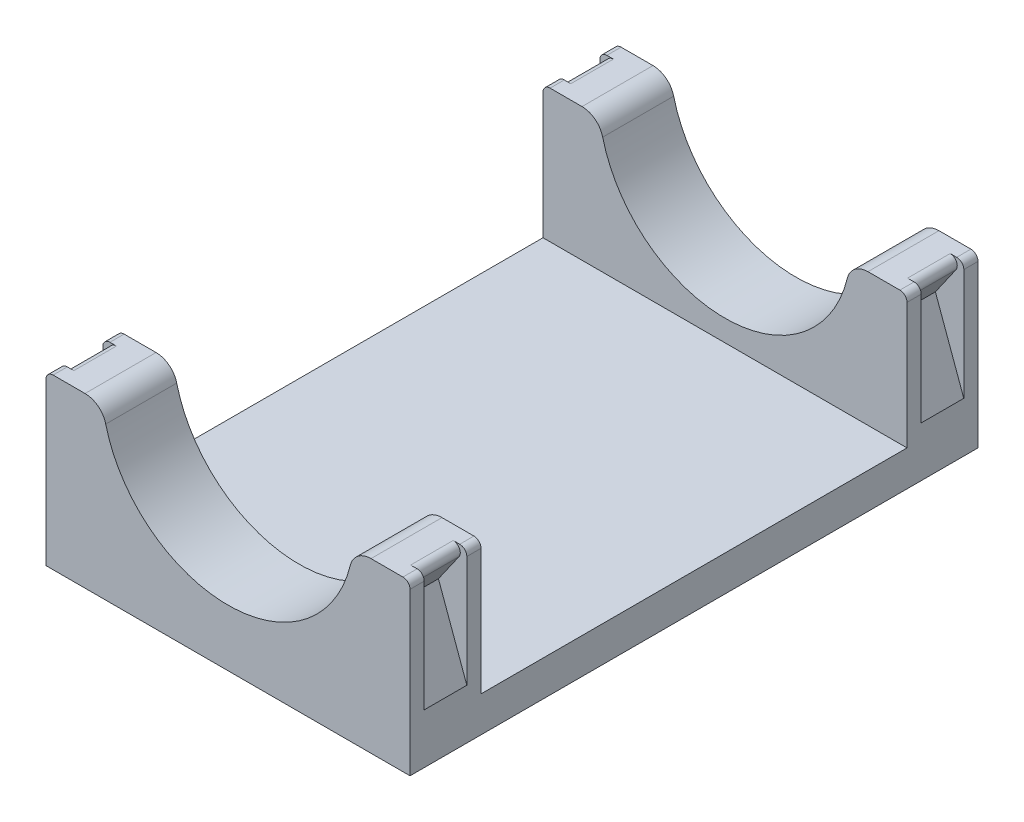
SolidWorks part; units mm, degrees
ref_plane "Front Plane" through (0, 0, 0) normal (0, 0, 1) x (1, 0, 0)
ref_plane "Top Plane" through (0, 0, 0) normal (0, 1, 0) x (1, 0, 0)
ref_plane "Right Plane" through (0, 0, 0) normal (1, 0, 0) x (0, 0, -1)
sketch "Sketch1" plane through (0, 0, 0) normal (0, 0, 1) x (1, 0, 0)
  line L0 (0, 0) -> (0, -25.75) construction
  line L1 (25.637, -25.75) -> (25.637, -2)
  line L2 (25.637, -2) -> (17.637, -2)
  line L3 (-25.637, -2) -> (-17.637, -2)
  line L4 (-25.637, -25.75) -> (-25.637, -2)
  line L5 (-25.637, -25.75) -> (25.637, -25.75)
  circle A0 centre (0, 0) radius 16.75 construction
  arc A1 (17.637, -2) -> (-17.637, -2) centre (0, 0) cw
  point P6 (0, -35.59)
  point P11 (0, -17.75)
  dimension "D1" = 33.5
  dimension "D2" = 1
  dimension "D3" = 8
  dimension "D4" = 2
  dimension "D5" = 8
extrude "Boss-Extrude1" add sketch "Sketch1" along normal mid plane 10 contours A1 L3 L4 L5 L1 L2
sketch "Sketch2" plane through (0, 0, 0) normal (0, 0, 1) x (1, 0, 0)
  line L0 (25.637, -2) -> (21.637, -7.7126)
  line L1 (21.637, -7.7126) -> (25.637, -18.7025)
  line L2 (25.637, -25.75) -> (25.637, -2) construction
  line L3 (25.637, -18.7025) -> (25.637, -2)
  line L4 (25.637, -2) -> (17.637, -2) construction
  dimension "D1" = 55
  dimension "D2" = 20
  dimension "D3" = 4
extrude "Cut-Extrude1" cut sketch "Sketch2" against normal mid plane 6
mirror "Mirror4" about plane through (0, 0, 0) normal (1, 0, 0) of "Cut-Extrude1"
fillet "Fillet2" radius 1 2 edges at (-25.637, -2, 0) (25.637, -2, 0)
fillet "Fillet3" radius 1 4 edges at (-25.637, -2, 4) (-25.637, -2, -4) (25.637, -2, -4) (25.637, -2, 4)
fillet "Fillet4" radius 3 2 edges at (17.637, -2, 0) (-17.637, -2, 0)
pattern_linear "LPattern1" count 2 spacing 70 along (0, 0, 1) of bodies 103
sketch "Sketch3" plane through (0, 0, 5) normal (0, 0, 1) x (1, 0, 0)
  line L0 (25.637, -25.75) -> (25.637, -3) construction
  line L1 (-25.637, -25.75) -> (25.637, -25.75)
  line L2 (-25.637, -25.75) -> (-25.637, -20.75)
  line L3 (-25.637, -20.75) -> (25.637, -20.75)
  line L4 (25.637, -25.75) -> (25.637, -20.75)
  dimension "D1" = 5
extrude "Boss-Extrude2" add sketch "Sketch3" along normal up to next
